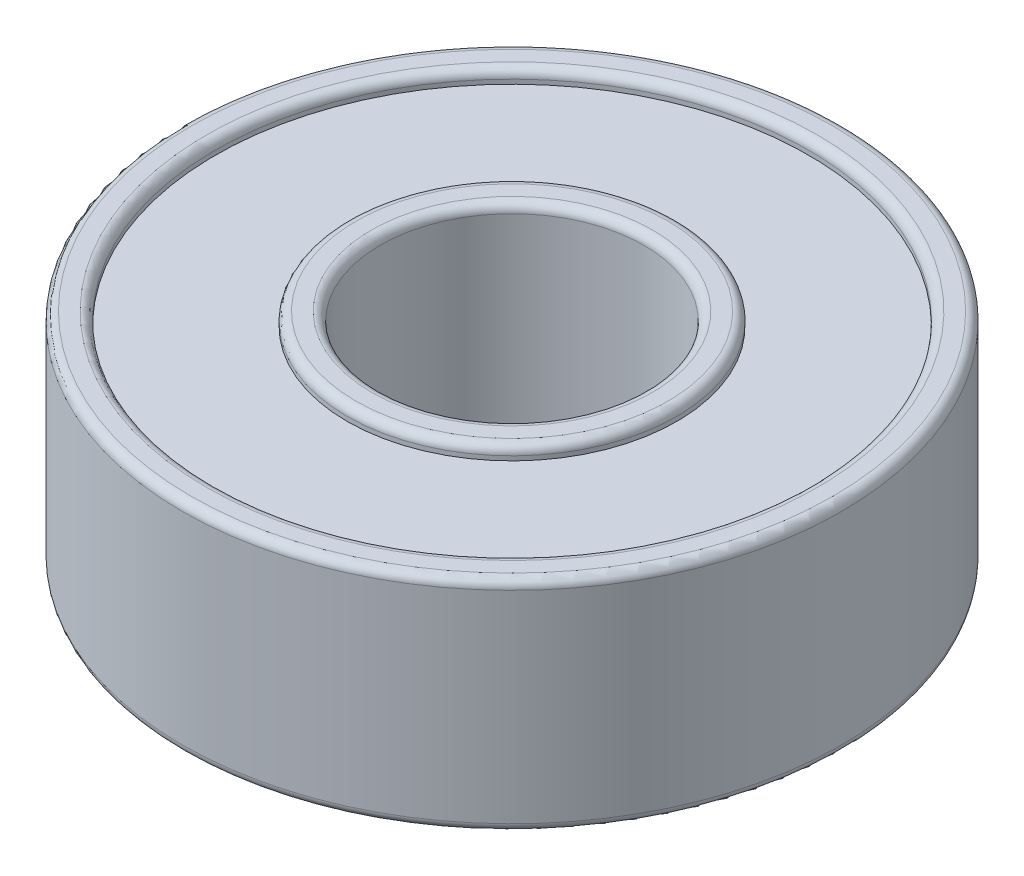
SolidWorks part; units mm, degrees
ref_plane "正面" through (0, 0, 0) normal (0, 0, 1) x (1, 0, 0)
ref_plane "平面" through (0, 0, 0) normal (0, 1, 0) x (1, 0, 0)
ref_plane "右側面" through (0, 0, 0) normal (1, 0, 0) x (0, 0, -1)
sketch "ｽｹｯﾁ1" plane through (0, 0, 0) normal (0, 1, 0) x (1, 0, 0)
  circle A0 centre (0, 0) radius 7.5
  circle A1 centre (0, 0) radius 3
  dimension "D1" = 15
  dimension "D2" = 6
extrude "ﾎﾞｽ - 押し出し1" add sketch "ｽｹｯﾁ1" along normal mid plane 5
sketch "ｽｹｯﾁ2" plane through (0, 2.5, 0) normal (0, 1, 0) x (1, 0, 0)
  circle A0 centre (0, 0) radius 3 construction
  circle A1 centre (0, 0) radius 7.5
  circle A2 centre (0, 0) radius 7.5
  circle A3 centre (0, 0) radius 3
  circle A4 centre (0, 0) radius 6.75
  circle A5 centre (0, 0) radius 3.75
  dimension "D1" = 0
  dimension "D2" = 0.75
  dimension "D3" = 0.75
extrude "ｶｯﾄ - 押し出し1" cut sketch "ｽｹｯﾁ2" against normal blind 0.3 contours A4 A5
mirror "ﾐﾗｰ1" about plane through (0, 0, 0) normal (0, 1, 0) of "ｶｯﾄ - 押し出し1"
fillet "ﾌｨﾚｯﾄ1" radius 0.2 8 edges at (0, -2.5, 3.75) (0, -2.5, 6.75) (0, 2.5, 3.75) (0, 2.5, 6.75) (0, -2.5, 3) (0, 2.5, 3) (0, -2.5, 7.5) (0, 2.5, 7.5)
